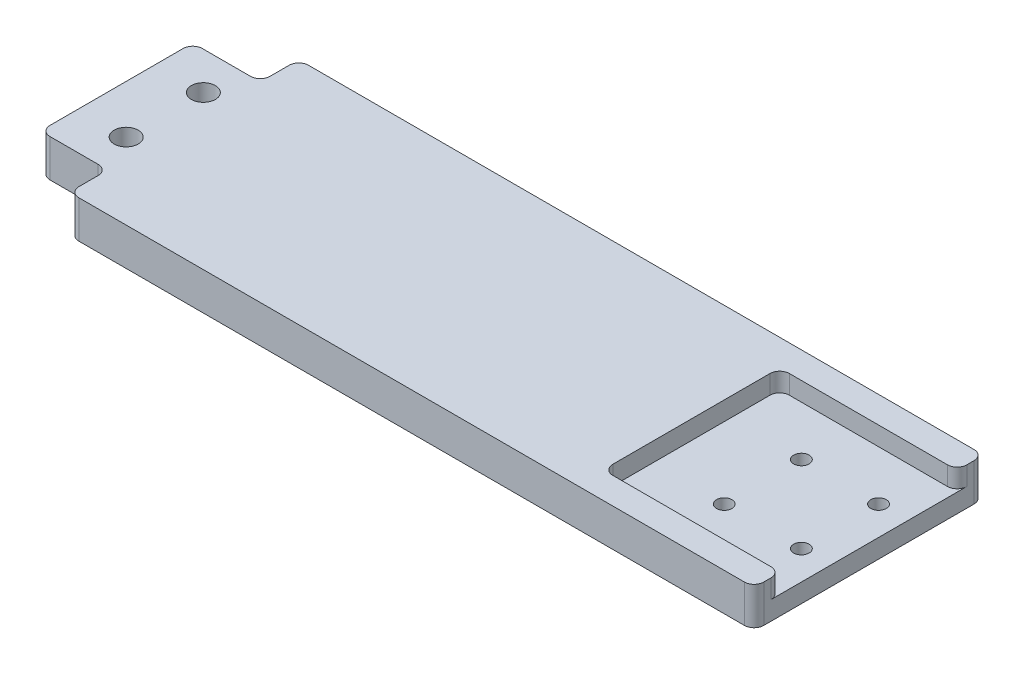
SolidWorks part; units mm, degrees
material "1.0503 (C45)"
ref_plane "Front Plane" through (0, 0, 0) normal (0, 0, 1) x (1, 0, 0)
ref_plane "Top Plane" through (0, 0, 0) normal (0, 1, 0) x (1, 0, 0)
ref_plane "Right Plane" through (0, 0, 0) normal (1, 0, 0) x (0, 0, -1)
sketch "Ref outline, front" plane through (0, 0, 0) normal (0, 1, 0) x (1, 0, 0)
  line L0 (0, 33.1008) -> (0, -39.9111) construction
  line L5 (-41.1596, 0) -> (51.6494, 0) construction
  line L6 (-33, 0) -> (-33, 11.9) construction
  line L7 (-33, 11.9) -> (24, 11.9) construction
  line L8 (24, 11.9) -> (27, 11.9) construction
  line L9 (30, 16) -> (33, 16) construction
  line L10 (33, 16) -> (33, 0) construction
  line L11 (27, 11.9) -> (27, 16) construction
  line L12 (27, 16) -> (30, 16) construction
  line L13 (-33, -11.9) -> (-33, 11.9)
  line L14 (-33, 11.9) -> (24, 11.9)
  line L15 (-33, -11.9) -> (24, -11.9)
  line L16 (27, 11.9) -> (27, 16)
  line L17 (27, -11.9) -> (27, -16)
  line L18 (27, 16) -> (30, 16)
  line L19 (27, -16) -> (30, -16)
  line L20 (30, 16) -> (33, 16)
  line L21 (30, -16) -> (33, -16)
  line L22 (33, 16) -> (33, -16)
  arc A1 (24, 11.9) -> (27, 11.9) centre (25.5, 11.9) ccw construction
  arc A2 (24, 11.9) -> (27, 11.9) centre (25.5, 11.9) ccw
  arc A3 (24, -11.9) -> (27, -11.9) centre (25.5, -11.9) cw
  dimension "D6" = 3
  dimension "D1" = 11.9
  dimension "D2" = 60
  dimension "D3" = 6
  dimension "D4" = 3
  dimension "D5" = 16
  dimension "D7" = 16
sketch "Ref hole and cut, Front" plane through (0, 0, 0) normal (0, 1, 0) x (1, 0, 0)
  line L0 (0, 0) -> (-36.1292, 0) construction
  line L1 (-33, 40.9324) -> (-33, -30.2811) construction
  line L2 (-33, 12) -> (-45.7821, 12) construction
  line L3 (24, 17.3256) -> (24, -6.6744) construction
  line L4 (-20, -26.6128) -> (-20, 37.264) construction
  line L5 (-33, 9.15) -> (-25, 9.15)
  line L6 (-33, -9.15) -> (-25, -9.15)
  line L7 (-25, 9.15) -> (-25, 15)
  line L8 (-25, -9.15) -> (-25, -15)
  line L9 (-25, 15) -> (-33, 15)
  line L10 (-25, -15) -> (-33, -15)
  line L11 (-33, 15) -> (-33, 9.15)
  line L12 (-33, -15) -> (-33, -9.15)
  point P8 (-33, 0)
  point P14 (-20, 4)
  point P20 (-20, 0)
  dimension "D1" = 44
  dimension "D2" = 4
  dimension "D3" = 18.3
  dimension "D4" = 8
  dimension "D5" = 30
  dimension "D6" = 33
sketch "Ref join cut, Front" plane through (0, 0, 0) normal (0, 1, 0) x (-1, 0, 0)
  line L0 (33, 9.15) -> (25, 9.15) construction
  line L2 (33, -9.15) -> (25, -9.15) construction
  line L5 (20, 200026.6128) -> (20, -200037.264) construction
  line L6 (17, 9.15) -> (35.4, 9.15)
  line L7 (17, 9.15) -> (17, -9.15)
  line L8 (17, -9.15) -> (35.4, -9.15)
  line L9 (35.4, 9.15) -> (35.4, -9.15)
  dimension "D1" = 3
  dimension "D2" = 18.4
sketch "Sketch5" plane through (0, 0, 0) normal (0, 1, 0) x (1, 0, 0)
  line L1 (-99, 11.9) -> (-17, 11.9)
  line L2 (-99, 11.9) -> (-99, -11.9)
  line L3 (-99, -11.9) -> (-17, -11.9)
  line L4 (-17, 11.9) -> (-17, -11.9)
  line L5 (-33, 11.9) -> (24, 11.9) construction
  line L6 (-33, -11.9) -> (24, -11.9) construction
  line L7 (-20, -200026.6128) -> (-20, 200037.264) construction
  line L8 (-25, 9.15) -> (-25, 15) construction
  dimension "D1" = 79
  dimension "D2" = 8
extrude "Boss-Extrude1" add sketch "Sketch5" along normal blind 3.9
hole_wizard "M2 Tapped Hole1" positions "Sketch6" profile "Sketch7" tap size "M2" standard "DIN" end condition through all
sketch "Sketch6" plane through (0, 3.9, 0) normal (0, 1, 0) x (1, 0, 0)
  point P0 (-20, 4)
sketch "Sketch7" plane through (-20, 3.9, -4) normal (1, 0, 0) x (0, 0, 1)
  line L0 (0, 0) -> (0, 3.9)
  line L1 (0, 3.9) -> (0.8, 3.9)
  line L2 (0.8, 3.9) -> (0.8, 0)
  line L5 (0.8, 0) -> (0, 0)
  line L11 (0, -6.35) -> (0, 107.95) construction
  dimension "Thru Tap Drill Dia." = 1.6
  dimension "Thru Tap Drill Depth" = 3.9
cosmetic thread "Hole Thread1" parameters "D2"=2
pattern_linear "LPattern1" count 2 spacing 8 along (0, 0, 1) count 2 spacing 8 along (-1, 0, 0) of "M2 Tapped Hole1"
cosmetic thread "Hole Thread2" parameters "D2"=2
cosmetic thread "Hole Thread3" parameters "D2"=2
cosmetic thread "Hole Thread4" parameters "D2"=2
extrude "Cut-Extrude2" cut sketch "Ref join cut, Front" against normal blind 1.95 from surface at 3.9 starting at face at (-20, 3.9, 4.8)
sketch "Sketch9" plane through (0, 0, 0) normal (0, 1, 0) x (1, 0, 0)
  line L0 (-200041.1596, 0) -> (200051.6494, 0) construction
  line L1 (-25, 9.15) -> (-10, 9.15)
  line L2 (-25, 9.15) -> (-25, 22.5)
  line L3 (-25, 22.5) -> (-10, 22.5)
  line L4 (-10, 9.15) -> (-10, 22.5)
  line L5 (-25, -9.15) -> (-10, -9.15)
  line L6 (-25, -9.15) -> (-25, -22.5)
  line L7 (-25, -22.5) -> (-10, -22.5)
  line L8 (-10, -9.15) -> (-10, -22.5)
  dimension "D1" = 45
  dimension "D2" = 15
  dimension "D3" = 22.5
extrude "Cut-Extrude3" [suppressed] cut sketch "Sketch9" along normal through all
sketch "Sketch17" [suppressed] plane through (0, 0, -9.1) normal (0, 0, 1) x (1, 0, 0)
  line L1 (-35, 1.9) -> (-25, 1.9)
  line L2 (-35, 1.9) -> (-35, 2.9)
  line L3 (-35, 2.9) -> (-25, 2.9)
  line L4 (-25, 1.9) -> (-25, 2.9)
extrude "Q&D1" [suppressed] cut sketch "Sketch17" against normal blind 0.05
sketch "Sketch18" [suppressed] plane through (-35, 0, 0) normal (1, 0, 0) x (0, 0, -1)
  line L0 (9.15, 2.9) -> (9.15, 1.9) construction
  line L1 (-9.1, 1.9) -> (9.15, 1.9)
  line L2 (-9.1, 1.9) -> (-9.1, 6.449)
  line L3 (-9.1, 6.449) -> (9.15, 6.449)
  line L4 (9.15, 1.9) -> (9.15, 6.449)
extrude "Q&D2" [suppressed] cut sketch "Sketch18" against normal blind 1 contours L3 L4 L1 L2
sketch "Sketch19" [suppressed] plane through (0, 0, 9.1) normal (0, 0, -1) x (-1, 0, 0)
  line L1 (25, 2.9) -> (36, 2.9)
  line L2 (25, 2.9) -> (25, 1.9)
  line L3 (25, 1.9) -> (36, 1.9)
  line L4 (36, 2.9) -> (36, 1.9)
extrude "Q&D3" [suppressed] cut sketch "Sketch19" against normal blind 0.05
fillet "Fillet3" [suppressed] radius 1
fillet "Fillet5" [suppressed] radius 1
fillet "Fillet1" [suppressed] radius 0.8
sketch "Sketch10" plane through (0, 3.9, 0) normal (0, 1, 0) x (1, 0, 0)
  line L0 (-72, 26.5292) -> (-72, -23.0742) construction
  line L1 (-20, -200026.6128) -> (-20, 200037.264) construction
  line L3 (-90, 34.1656) -> (-90, -26.2467) construction
  line L4 (200000, 0) -> (-200036.1292, 0) construction
  point P6 (-90, 4)
  dimension "D2" = 18
  dimension "D1" = 52
  dimension "D3" = 4
hole_wizard "M3 Tapped Hole2" positions "Sketch11" profile "Sketch12" tap size "M3" standard "DIN" end condition through all
sketch "Sketch11" plane through (0, 3.9, 0) normal (0, 1, 0) x (1, 0, 0)
  point P0 (-90, 4)
sketch "Sketch12" plane through (-90, 3.9, -4) normal (1, 0, 0) x (0, 0, 1)
  line L0 (0, 0) -> (0, 3.9)
  line L1 (0, 3.9) -> (1.25, 3.9)
  line L2 (1.25, 3.9) -> (1.25, 0)
  line L5 (1.25, 0) -> (0, 0)
  line L11 (0, -6.35) -> (0, 107.95) construction
  dimension "Thru Tap Drill Dia." = 2.5
  dimension "Thru Tap Drill Depth" = 3.9
cosmetic thread "Hole Thread5" parameters "D2"=3
pattern_linear "LPattern2" count 2 spacing 8 along (0, 0, 1) of "M3 Tapped Hole2"
cosmetic thread "Hole Thread6" parameters "D2"=3
sketch "Sketch13" plane through (0, 3.9, 0) normal (0, 1, 0) x (1, 0, 0)
  line L0 (-88, -11.9) -> (-88, -7.9)
  line L1 (-99, -11.9) -> (-17, -11.9) construction
  line L2 (-88, -7.9) -> (-95, -7.9)
  line L3 (-95, -7.9) -> (-95, 7.9)
  line L4 (-95, 7.9) -> (-88, 7.9)
  line L5 (-88, 7.9) -> (-88, 11.9)
  line L6 (-17, 11.9) -> (-99, 11.9) construction
  line L7 (-99, 11.9) -> (-99, -11.9) construction
  line L8 (-88, -11.9) -> (-99, -11.9)
  line L9 (-99, -11.9) -> (-99, 11.9)
  line L10 (-99, 11.9) -> (-88, 11.9)
  circle A0 centre (-90, -4) radius 1.25 construction
  point P12 (-99, 0)
  point P13 (-95, 0)
  dimension "D1" = 5
  dimension "D2" = 4
  dimension "D3" = 7
extrude "Cut-Extrude4" cut sketch "Sketch13" against normal through all
fillet "Fillet4" radius 1 6 edges at (-88, 1.95, 11.9) (-88, 1.95, -7.9) (-88, 1.95, -11.9) (-95, 1.95, -7.9) (-95, 1.95, 7.9) (-88, 1.95, 7.9)
fillet "Fillet6" radius 1 6 edges at (-17, 1.95, 11.9) (-17, 2.925, 9.15) (-35.4, 2.925, 9.15) (-35.4, 2.925, -9.15) (-17, 2.925, -9.15) (-17, 1.95, -11.9)
